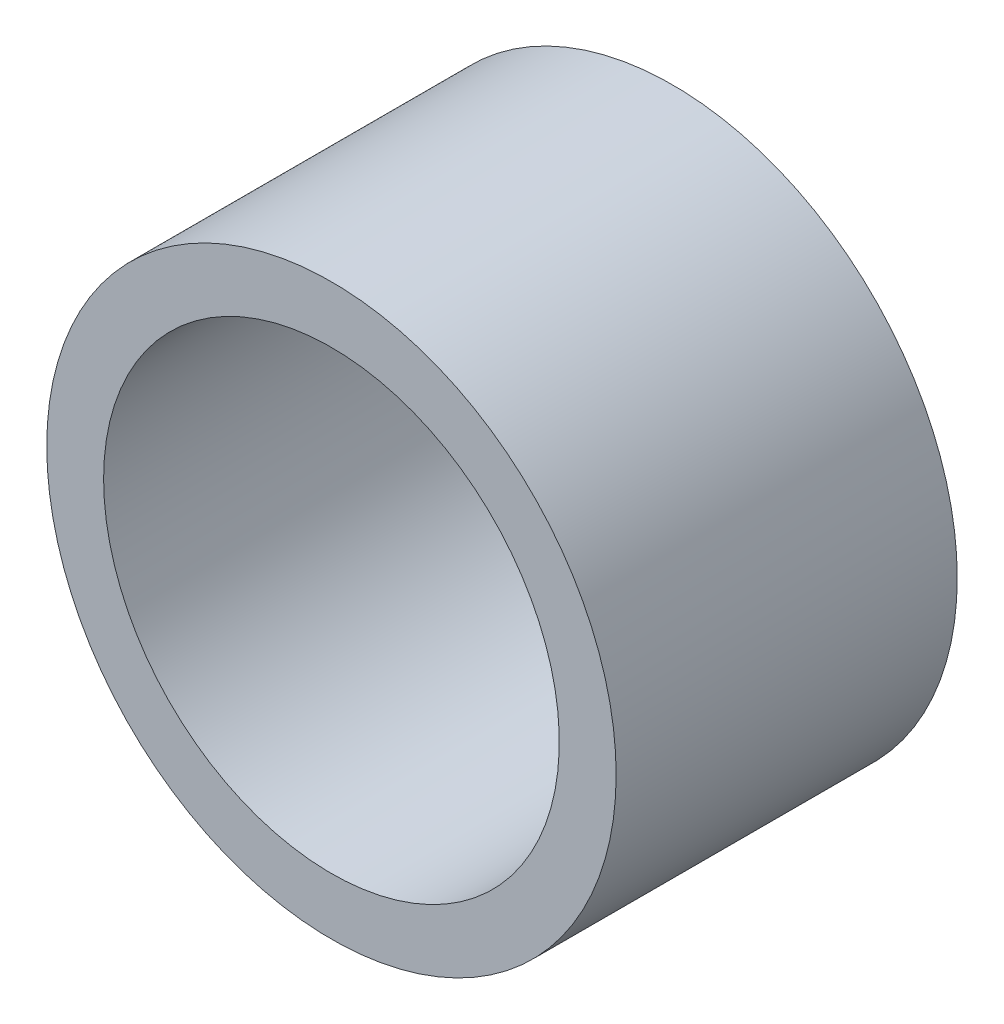
SolidWorks part; units mm, degrees
material "Manganese Bronze"
ref_plane "Front Plane" through (0, 0, 0) normal (0, 0, 1) x (1, 0, 0)
ref_plane "Top Plane" through (0, 0, 0) normal (0, 1, 0) x (1, 0, 0)
ref_plane "Right Plane" through (0, 0, 0) normal (1, 0, 0) x (0, 0, -1)
sketch "Sketch1" plane through (0, 0, 0) normal (0, 0, 1) x (1, 0, 0)
  circle A0 centre (0, 0) radius 15.9004
  circle A1 centre (0, 0) radius 12.7254
  dimension "D1" = 31.8008
  dimension "ID" = 25.4508
extrude "Extrude1" add sketch "Sketch1" along normal mid plane 19.05
sketch "Sketch2" plane through (0, 0, 0) normal (1, 0, 0) x (0, 0, -1)
  line L0 (-9.525, -12.7254) -> (9.525, -12.7254) construction
  line L3 (9.525, 12.7254) -> (-9.525, 12.7254) construction
  line L5 (-9.525, -12.7254) -> (9.525, -12.7254)
  line L6 (9.525, 12.7254) -> (-9.525, 12.7254)
sketch "Sketch4" plane through (0, 0, 9.525) normal (0, 0, 1) x (1, 0, 0)
  line L0 (0, 0) -> (-8.9982, 8.9982)
  line L1 (0, -13.97) -> (0, 13.97) construction
  circle A0 centre (0, 0) radius 12.7254 construction
  dimension "D1" = 45
